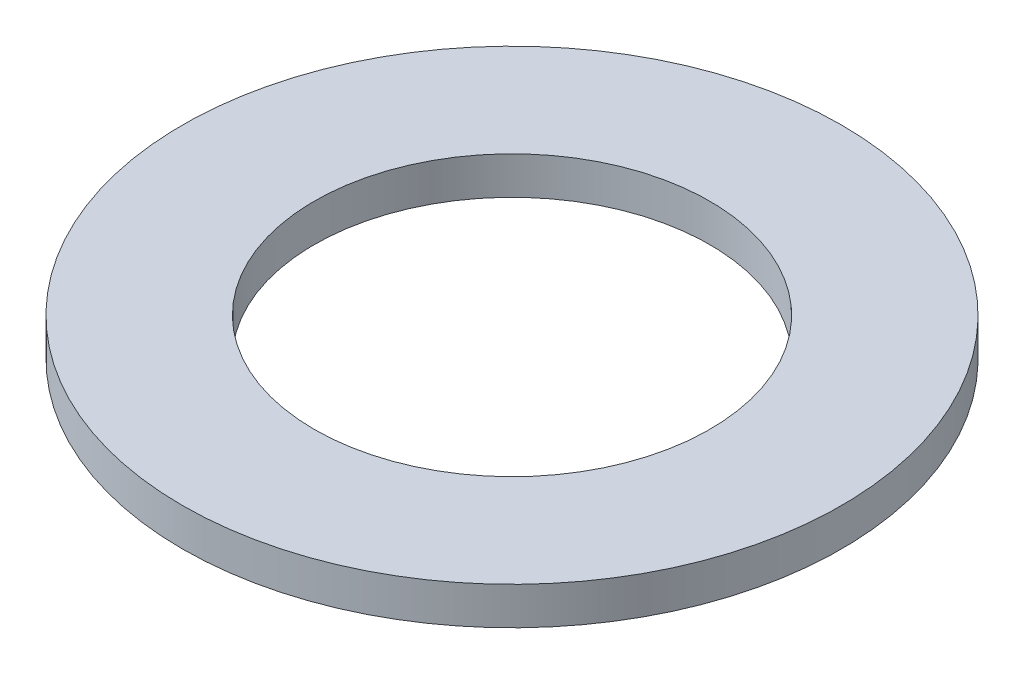
SolidWorks part; units mm, degrees
material "1.0406 (C25)"
ref_plane "Płaszczyzna przednia" through (0, 0, 0) normal (0, 0, 1) x (1, 0, 0)
ref_plane "Płaszczyzna górna" through (0, 0, 0) normal (0, 1, 0) x (1, 0, 0)
ref_plane "Płaszczyzna prawa" through (0, 0, 0) normal (1, 0, 0) x (0, 0, -1)
sketch "Szkic1" plane through (0, 0, 0) normal (0, 1, 0) x (1, 0, 0)
  circle A0 centre (0, 0) radius 10.5
  circle A1 centre (0, 0) radius 17.5
  dimension "D1" = 21
  dimension "D2" = 35
extrude "Dodanie-wyciągnięcie1" add sketch "Szkic1" along normal blind 2
